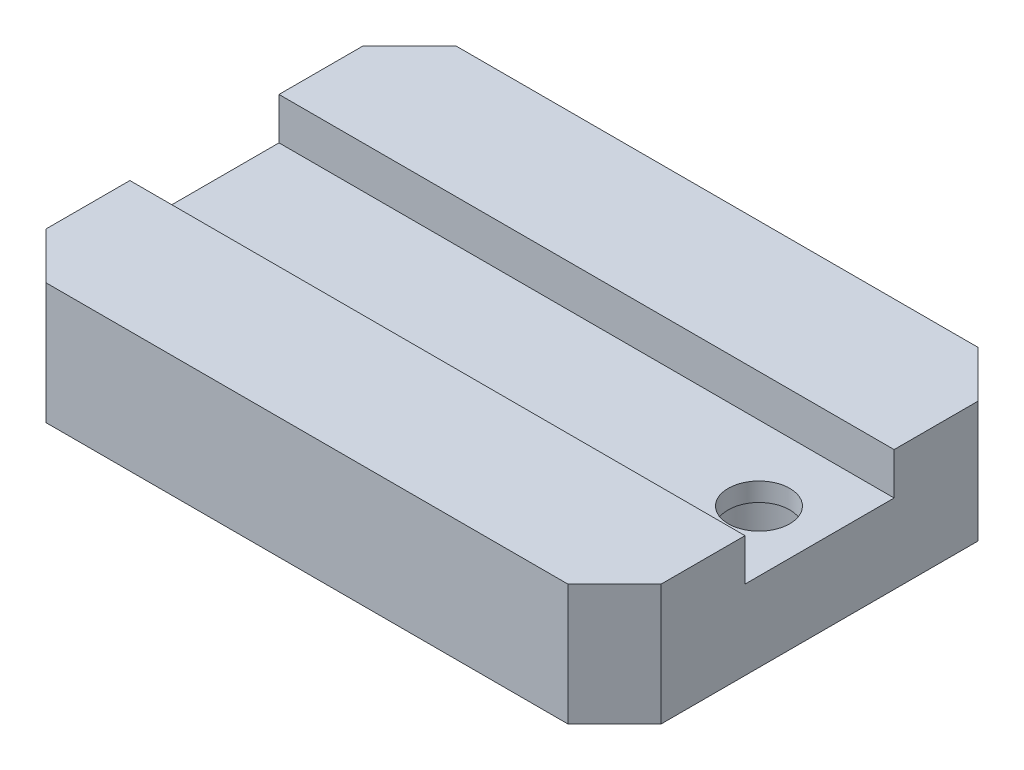
SolidWorks part; units mm, degrees
material "AISI 1045 Aço, trefilado"
ref_plane "Plano frontal" through (0, 0, 0) normal (0, 0, 1) x (1, 0, 0)
ref_plane "Plano superior" through (0, 0, 0) normal (0, 1, 0) x (1, 0, 0)
ref_plane "Plano direito" through (0, 0, 0) normal (1, 0, 0) x (0, 0, -1)
sketch "Esboço1" plane through (0, 0, 0) normal (0, 0, 1) x (1, 0, 0)
  line L1 (0, 0) -> (66, 0)
  line L2 (0, 0) -> (0, -13)
  line L3 (0, -13) -> (66, -13)
  line L4 (66, 0) -> (66, -13)
  dimension "D1" = 13
  dimension "D2" = 66
extrude "Ressalto-extrusão1" add sketch "Esboço1" along normal blind 44
sketch "Esboço2" plane through (0, 0, 0) normal (0, 1, 0) x (1, 0, 0)
  line L0 (0, -14) -> (66, -14)
  line L1 (0, -44) -> (0, 0) construction
  line L2 (66, -44) -> (66, 0) construction
  line L3 (0, -30) -> (66, -30)
  line L4 (66, 0) -> (0, 0) construction
  line L5 (0, -14) -> (0, -30)
  line L6 (66, -14) -> (66, -30)
  dimension "D1" = 16
  dimension "D2" = 14
extrude "Corte-extrusão1" cut sketch "Esboço2" against normal blind 4.5
chamfer "Chanfro1" distance 5 angle 45 4 edges at (0, -6.5, 0) (66, -6.5, 0) (66, -6.5, 44) (0, -6.5, 44)
sketch "Esboço4" plane through (0, -4.5, 0) normal (0, 1, 0) x (1, 0, 0)
  line L0 (0, -30) -> (66, -30) construction
  line L1 (66, -30) -> (66, -14) construction
  circle A0 centre (59.5, -22) radius 3.3
  dimension "D1" = 6.6
  dimension "D2" = 8
  dimension "D3" = 6.5
extrude "Corte-extrusão2" cut sketch "Esboço4" against normal blind 2
sketch "Esboço5" plane through (0, -13, 0) normal (0, -1, 0) x (1, 0, 0)
  line L2 (66, 39) -> (66, 5) construction
  circle A0 centre (59.5, 22) radius 5.5
  dimension "D3" = 11
  dimension "D5" = 6.5
extrude "Corte-extrusão3" cut sketch "Esboço5" against normal blind 6.5
